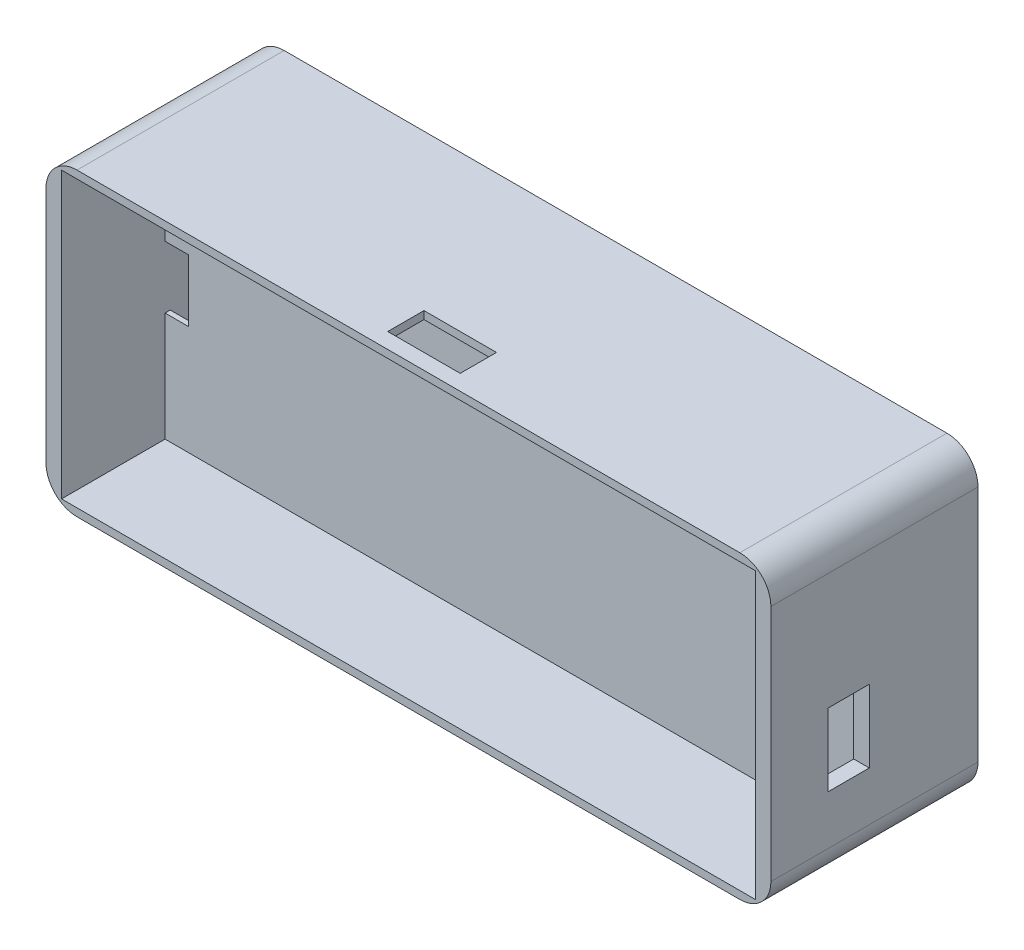
SolidWorks part; units mm, degrees
ref_plane "前视基准面" through (0, 0, 0) normal (0, 0, 1) x (1, 0, 0)
ref_plane "上视基准面" through (0, 0, 0) normal (0, 1, 0) x (1, 0, 0)
ref_plane "右视基准面" through (0, 0, 0) normal (1, 0, 0) x (0, 0, -1)
sketch "草图1" plane through (0, 0, 0) normal (0, 0, 1) x (1, 0, 0)
  line L1 (-64, 29) -> (64, 29)
  line L2 (-70, 23) -> (-70, -23)
  line L3 (-64, -29) -> (64, -29)
  line L4 (70, 23) -> (70, -23)
  line L5 (-70, 29) -> (70, -29) construction
  line L6 (-70, -29) -> (70, 29) construction
  line L7 (-67, 16.5) -> (67, 16.5)
  line L8 (-67, 16.5) -> (-67, -16.5)
  line L9 (-67, -16.5) -> (67, -16.5)
  line L10 (67, 16.5) -> (67, -16.5)
  line L11 (-67, 16.5) -> (67, -16.5) construction
  line L12 (-67, -16.5) -> (67, 16.5) construction
  arc A0 (64, 29) -> (70, 23) centre (64, 23) cw
  arc A1 (70, -23) -> (64, -29) centre (64, -23) cw
  arc A2 (-64, -29) -> (-70, -23) centre (-64, -23) cw
  arc A3 (-70, 23) -> (-64, 29) centre (-64, 23) cw
  point P0 (0, 0)
  point P18 (0, 0)
  dimension "D3" = 6
  dimension "D1" = 140
  dimension "D2" = 58
  dimension "D4" = 33
  dimension "D5" = 134
extrude "凸台-拉伸1" add sketch "草图1" along normal blind 40
sketch "草图2" plane through (0, 0, 0) normal (0, 0, 1) x (1, 0, 0)
  line L1 (67, 16.5) -> (-67, 16.5)
  line L2 (67, 16.5) -> (67, -16.5)
  line L3 (67, -16.5) -> (-67, -16.5)
  line L4 (-67, 16.5) -> (-67, -16.5)
  line L5 (67, 16.5) -> (-67, -16.5) construction
  line L6 (67, -16.5) -> (-67, 16.5) construction
  point P0 (0, 0)
extrude "凸台-拉伸2" add sketch "草图2" along normal blind 3 from offset 19
sketch "草图3" plane through (0, 0, 19) normal (0, 0, -1) x (-1, 0, 0)
  line L0 (0, 0) -> (15.9741, 0) construction
  line L1 (62.5, 5.5903) -> (62.5, -6.4097)
  line L2 (67, 16.5) -> (67, -16.5) construction
  line L3 (62.5, 5.5903) -> (67, 5.5903)
  line L4 (67, 16.5) -> (67, -16.5) construction
  line L5 (67, 5.5903) -> (67, -6.4097)
  line L6 (67, -6.4097) -> (62.5, -6.4097)
  dimension "D1" = 4.5
  dimension "D2" = 12
extrude "切除-拉伸1" cut sketch "草图3" against normal through all
sketch "草图4" plane through (0, 0, 40) normal (0, 0, 1) x (1, 0, 0)
  line L1 (-67, 27.5) -> (67, 27.5)
  line L2 (-67, 27.5) -> (-67, -27.5)
  line L3 (-67, -27.5) -> (67, -27.5)
  line L4 (67, 27.5) -> (67, -27.5)
  line L5 (-67, 27.5) -> (67, -27.5) construction
  line L6 (-67, -27.5) -> (67, 27.5) construction
  point P0 (0, 0)
  dimension "D1" = 55
  dimension "D2" = 134
extrude "切除-拉伸2" cut sketch "草图4" against normal blind 20
sketch "草图6" plane through (0, 29, 0) normal (0, 1, 0) x (1, 0, 0)
  line L0 (0, 0) -> (0, -45.5631) construction
  line L1 (64, 0) -> (-64, 0) construction
  line L2 (64, -40) -> (-64, -40) construction
  line L3 (-7, -30) -> (7, -30)
  line L4 (-7, -30) -> (-7, -37)
  line L5 (-7, -37) -> (7, -37)
  line L6 (7, -30) -> (7, -37)
  line L7 (-7, -30) -> (7, -37) construction
  line L8 (-7, -37) -> (7, -30) construction
  point P4 (0, -33.5)
  dimension "D1" = 14
  dimension "D2" = 3
  dimension "D3" = 7
extrude "切除-拉伸3" cut sketch "草图6" against normal blind 10
sketch "草图7" plane through (67, 0, 0) normal (-1, 0, 0) x (0, 0, 1)
  line L0 (20, -27.5) -> (40, -27.5) construction
  line L1 (21, 0.5) -> (29, 0.5)
  line L2 (21, 0.5) -> (21, -13.5)
  line L3 (21, -13.5) -> (29, -13.5)
  line L4 (29, 0.5) -> (29, -13.5)
  line L5 (21, 0.5) -> (29, -13.5) construction
  line L6 (21, -13.5) -> (29, 0.5) construction
  line L8 (20, -27.5) -> (20, 27.5) construction
  point P0 (25, -6.5)
  dimension "D1" = 14
  dimension "D2" = 14
  dimension "D3" = 8
  dimension "D4" = 9
extrude "切除-拉伸4" cut sketch "草图7" against normal blind 10
sketch "草图8" plane through (0, 0, 0) normal (0, 0, -1) x (-1, 0, 0)
  line L0 (-0.5, 0) -> (91.881, 0) construction
  line L1 (0.2391, 1.6378) -> (0.2391, 61.9841) construction
  line L2 (-67, 16.5) -> (67, 16.5) construction
  line L4 (-66.2609, 25.5) -> (66.7391, 25.5)
  line L5 (-66.2609, 25.5) -> (-66.2609, 22.5)
  line L6 (-66.2609, 22.5) -> (66.7391, 22.5)
  line L7 (66.7391, 25.5) -> (66.7391, 22.5)
  line L8 (-66.2609, 25.5) -> (66.7391, 22.5) construction
  line L9 (-66.2609, 22.5) -> (66.7391, 25.5) construction
  line L10 (66.7391, -25.5) -> (66.7391, -22.5)
  line L11 (-66.2609, -22.5) -> (66.7391, -22.5)
  line L12 (-66.2609, -25.5) -> (-66.2609, -22.5)
  line L13 (-66.2609, -25.5) -> (66.7391, -25.5)
  point P2 (0.2391, 24)
  point P7 (0.2391, 25.6036)
  dimension "D1" = 133
  dimension "D2" = 3
  dimension "D3" = 6
  dimension "D4" = 22.5
extrude "切除-拉伸5" cut sketch "草图8" against normal blind 10
